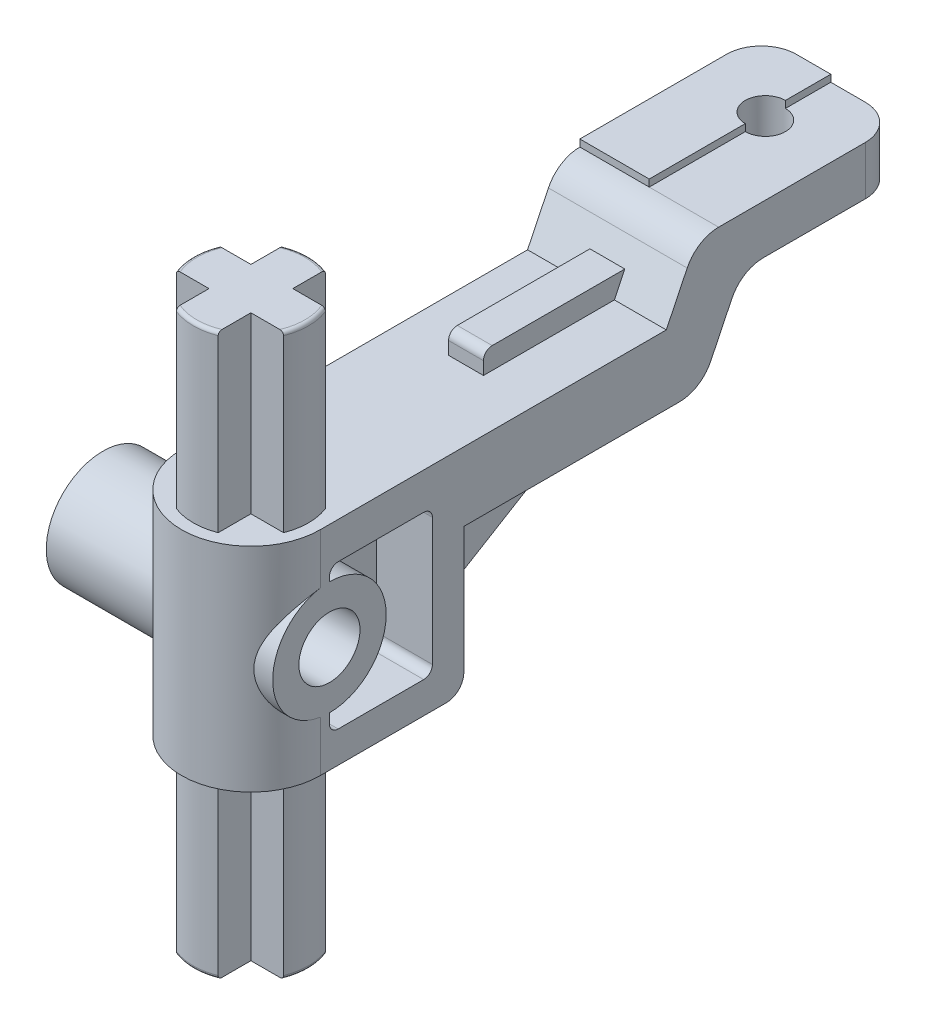
SolidWorks part; units mm, degrees
ref_plane "Alzado" through (0, 0, 0) normal (0, 0, 1) x (1, 0, 0)
ref_plane "Planta" through (0, 0, 0) normal (0, 1, 0) x (1, 0, 0)
ref_plane "Vista lateral" through (0, 0, 0) normal (1, 0, 0) x (0, 0, -1)
sketch "Croquis1" plane through (0, 0, 0) normal (1, 0, 0) x (0, 0, -1)
  line L0 (0, 0) -> (0, 12.2)
  line L1 (0, 12.2) -> (23.8, 12.2)
  line L2 (23.8, 12.2) -> (25.5432, 15.8)
  line L3 (25.5432, 15.8) -> (37.2, 15.8)
  line L4 (37.2, 15.8) -> (37.2, 13)
  line L5 (37.2, 13) -> (28.1, 13)
  line L6 (28.1, 13) -> (25.8, 8.25)
  line L7 (25.8, 8.25) -> (12.2, 8.25)
  line L8 (12.2, 8.25) -> (12.2, 0)
  line L9 (12.2, 0) -> (0, 0)
  dimension "D1" = 37.2
  dimension "D2" = 15.8
  dimension "D3" = 12.2
  dimension "D4" = 12.2
  dimension "D5" = 25.8
  dimension "D6" = 8.25
  dimension "D7" = 2.8
  dimension "D8" = 23.8
  dimension "D9" = 9.1
extrude "Saliente-Extruir1" add sketch "Croquis1" along normal blind 7.95
sketch "Croquis2" plane through (0, 15.8, 0) normal (0, 1, 0) x (1, 0, 0)
  line L0 (0, 23.8) -> (0, 0) construction
  line L1 (7.95, 23.8) -> (7.95, 0) construction
  line L2 (7.95, 0) -> (0, 0) construction
  line L3 (0, 3.975) -> (0, -1.0234)
  line L4 (0, -1.0234) -> (7.95, -1.0234)
  line L5 (7.95, -1.0234) -> (7.95, 3.975)
  arc A0 (0, 3.975) -> (7.95, 3.975) centre (3.975, 3.975) ccw
extrude "Cortar-Extruir1" cut sketch "Croquis2" against normal through all
ref_plane "Plano1" through (3.975, 0, 0) normal (-1, 0, 0) x (0, 0, 1)
sketch "Croquis3" plane through (3.975, 0, 0) normal (-1, 0, 0) x (0, 0, 1)
  line L0 (-23.8, 12.2) -> (-23.8, 8.25) construction
  line L1 (-12.2, 8.25) -> (-25.8, 8.25) construction
  line L2 (-23.8, 8.25) -> (-12.2, 1.25)
  line L3 (-12.2, 0) -> (-12.2, 8.25) construction
  line L4 (-12.2, 1.25) -> (-12.2, 8.25)
  line L5 (-12.2, 8.25) -> (-23.8, 8.25)
  dimension "D1" = 7
extrude "Saliente-Extruir2" add sketch "Croquis3" along normal mid plane 1.9
fillet "Redondeo1" radius 2 5 edges at (7.95, 14.4, -37.2) (0, 14.4, -37.2) (3.975, 13, -28.1) (3.975, 15.8, -25.5432) (3.975, 8.25, -25.8)
sketch "Croquis5" plane through (3.975, 0, 0) normal (-1, 0, 0) x (0, 0, 1)
  line L0 (-24.3984, 8.25) -> (-24.3984, 13.4358) construction
  line L1 (-24.9968, 14.6716) -> (-23.8, 12.2) construction
  line L2 (-24.3984, 13.4358) -> (-16.3, 13.4358)
  line L3 (-16.3, 13.4358) -> (-16.3, 10.4358)
  line L4 (-16.3, 10.4358) -> (-24.3984, 10.4358)
  line L5 (-12.2, 8.25) -> (-24.5463, 8.25) construction
  line L6 (-24.3984, 13.4358) -> (-24.3984, 10.4358)
  line L7 (-37.2, 13) -> (-37.2, 15.8) construction
  dimension "D1" = 3
  dimension "D2" = 20.9
extrude "Saliente-Extruir3" add sketch "Croquis5" along normal mid plane 2
fillet "Redondeo2" radius 0.5 1 edges at (3.975, 13.4358, -16.3)
fillet "Redondeo3" radius 1 1 edges at (3.975, 0, -12.2)
ref_plane "Plano2" through (0, 6.1, 0) normal (0, 1, 0) x (1, 0, 0)
sketch "Croquis6" plane through (0, 6.1, 0) normal (0, 1, 0) x (1, 0, 0)
  line L0 (2.775, 7.0491) -> (2.775, 5.175)
  line L1 (2.775, 3.975) -> (5.175, 3.975) construction
  line L2 (5.175, 5.175) -> (5.175, 7.0491)
  line L3 (3.975, 7.275) -> (3.975, 3.975) construction
  line L4 (7.0491, 5.175) -> (5.175, 5.175)
  line L5 (5.175, 2.775) -> (7.0491, 2.775)
  line L6 (5.175, 0.9009) -> (5.175, 2.775)
  line L7 (2.775, 2.775) -> (2.775, 0.9009)
  line L8 (0.9009, 2.775) -> (2.775, 2.775)
  line L9 (2.775, 5.175) -> (0.9009, 5.175)
  arc A0 (5.175, 7.0491) -> (2.775, 7.0491) centre (3.975, 3.975) ccw
  arc A1 (0, 3.975) -> (7.95, 3.975) centre (3.975, 3.975) ccw construction
  arc A2 (7.0491, 2.775) -> (7.0491, 5.175) centre (3.975, 3.975) ccw
  arc A3 (2.775, 0.9009) -> (5.175, 0.9009) centre (3.975, 3.975) ccw
  arc A4 (0.9009, 5.175) -> (0.9009, 2.775) centre (3.975, 3.975) ccw
  point P24 (3.975, 3.975)
  dimension "D1" = 6.6
  dimension "D2" = 2.4
  dimension "D3" = 1.2
  dimension "D4" = 4
extrude "Saliente-Extruir5" add sketch "Croquis6" along normal mid plane 32.15
sketch "Croquis8" plane through (0, 15.8, 0) normal (0, 1, 0) x (1, 0, 0)
  line L0 (3.975, 37.2) -> (5.95, 37.2)
  line L1 (5.95, 37.2) -> (2, 37.2) construction
  line L2 (5.95, 37.2) -> (7.95, 37.2)
  line L3 (7.95, 26.7969) -> (7.95, 37.2)
  line L4 (3.975, 37.2) -> (3.975, 26.7969)
  line L5 (0, 26.7969) -> (7.95, 26.7969) construction
  line L6 (3.975, 26.7969) -> (7.95, 26.7969)
extrude "Saliente-Extruir6" add sketch "Croquis8" along normal blind 0.4 and the other way up to vertex
fillet "Redondeo4" radius 2 1 edges at (7.95, 14.6, -37.2)
sketch "Croquis9" plane through (0, 16.2, 0) normal (0, 1, 0) x (1, 0, 0)
  line L0 (3.975, 37.2) -> (3.975, 26.7969) construction
  circle A0 centre (3.975, 33.45) radius 1.35
  dimension "D1" = 2.7
  dimension "D2" = 3.75
extrude "Cortar-Extruir2" cut sketch "Croquis9" against normal up to next
fillet "Redondeo5" radius 0.2 8 edges at (0.675, -9.975, -3.975) (3.975, -9.975, -0.675) (7.275, -9.975, -3.975) (3.975, -9.975, -7.275) (7.275, 22.175, -3.975) (3.975, 22.175, -0.675) (0.675, 22.175, -3.975) (3.975, 22.175, -7.275)
ref_plane "Plano4" through (3.975, 0, 0) normal (1, 0, 0) x (0, 0, -1)
sketch "Croquis10" plane through (3.975, 0, 0) normal (1, 0, 0) x (0, 0, -1)
  line L0 (12.2, 1) -> (12.2, 8.25) construction
  circle A0 centre (4.5, 6.1) radius 3.25
  dimension "D1" = 6.5
  dimension "D2" = 7.7
extrude "Saliente-Extruir7" add sketch "Croquis10" along normal blind 9 and the other way up to surface other way up to face at (0, 9.6767, -21.242)
sketch "Croquis11" plane through (0, 0, 0) normal (-1, 0, 0) x (0, 0, 1)
  line L0 (-10.4, 10.1) -> (-4.5, 10.1)
  line L1 (-10.4, 10.1) -> (-10.4, 1.8)
  line L2 (-10.4, 1.8) -> (-4.5, 1.8)
  line L4 (-4.5, 2.85) -> (-4.5, 1.8)
  line L6 (-4.5, 10.1) -> (-4.5, 9.35)
  line L7 (-12.2, 1) -> (-12.2, 8.25) construction
  line L8 (-3.975, 0) -> (-11.2, 0) construction
  arc A0 (-4.5, 9.35) -> (-4.5, 2.85) centre (-4.5, 6.1) ccw
  arc A1 (-3.975, 2.8927) -> (-3.975, 9.3073) centre (-4.5, 6.1) ccw construction
  dimension "D1" = 1.8
  dimension "D2" = 1.8
  dimension "D3" = 8.3
extrude "Cortar-Extruir3" cut sketch "Croquis11" against normal blind 3.2
fillet "Redondeo6" radius 0.5 4 edges at (1.6, 1.8, -4.5) (1.6, 1.8, -10.4) (1.6, 10.1, -10.4) (1.6, 10.1, -4.5)
mirror "Simetría4" about plane through (3.975, 0, 0) normal (1, 0, 0) of "Redondeo6", "Cortar-Extruir3"
sketch "Croquis12" plane through (12.975, 0, 0) normal (1, 0, 0) x (0, 0, -1)
  circle A0 centre (4.5, 6.1) radius 1.75
  circle A1 centre (4.5, 6.1) radius 3.25 construction
  dimension "D1" = 3.5
extrude "Cortar-Extruir4" cut sketch "Croquis12" against normal up to next
ref_plane "Plano5" through (-10, 0, 0) normal (-1, 0, 0) x (0, 0, 1)
mirror "Simetría6" about plane through (-10, 0, 0) normal (-1, 0, 0) of bodies 114
ref_plane "Plano6" through (-10, 0, 0) normal (1, 0, 0) x (0, 0, -1)
sketch "Croquis13" plane through (-10, 0, 0) normal (1, 0, 0) x (0, 0, -1)
  line L1 (-0.968, -11.2574) -> (40.1222, -11.2574)
  line L2 (-0.968, -11.2574) -> (-0.968, 23.6758)
  line L3 (-0.968, 23.6758) -> (40.1222, 23.6758)
  line L4 (40.1222, -11.2574) -> (40.1222, 23.6758)
extrude "Cortar-Extruir5" cut sketch "Croquis13" along normal blind 33 contours L3 L4 L1 L2
sketch "Croquis14" plane through (0, 16.2, 0) normal (0, 1, 0) x (1, 0, 0)
  circle A0 centre (-23.975, 33.45) radius 1.35
extrude "Saliente-Extruir8" add sketch "Croquis14" against normal up to vertex
sketch "Croquis15" plane through (0, 16.2, 0) normal (0, 1, 0) x (1, 0, 0)
  line L0 (-23.975, 37.2) -> (-23.975, 34.8) construction
  line L1 (-23.975, 35.781) -> (-22.1213, 35.781)
  line L2 (-23.975, 35.781) -> (-23.975, 31.1416)
  line L3 (-23.975, 31.1416) -> (-22.1213, 31.1416)
  line L4 (-22.1213, 35.781) -> (-22.1213, 31.1416)
extrude "Cortar-Extruir6" cut sketch "Croquis15" against normal up to surface (0.4 mm away) up to face at (-22.3051, 15.8, -32.9297)
sketch "Croquis16" plane through (0, 16.2, 0) normal (0, 1, 0) x (1, 0, 0)
  circle A0 centre (-23.975, 33.45) radius 1.15
  dimension "D1" = 2.3
extrude "Cortar-Extruir7" cut sketch "Croquis16" against normal up to vertex
